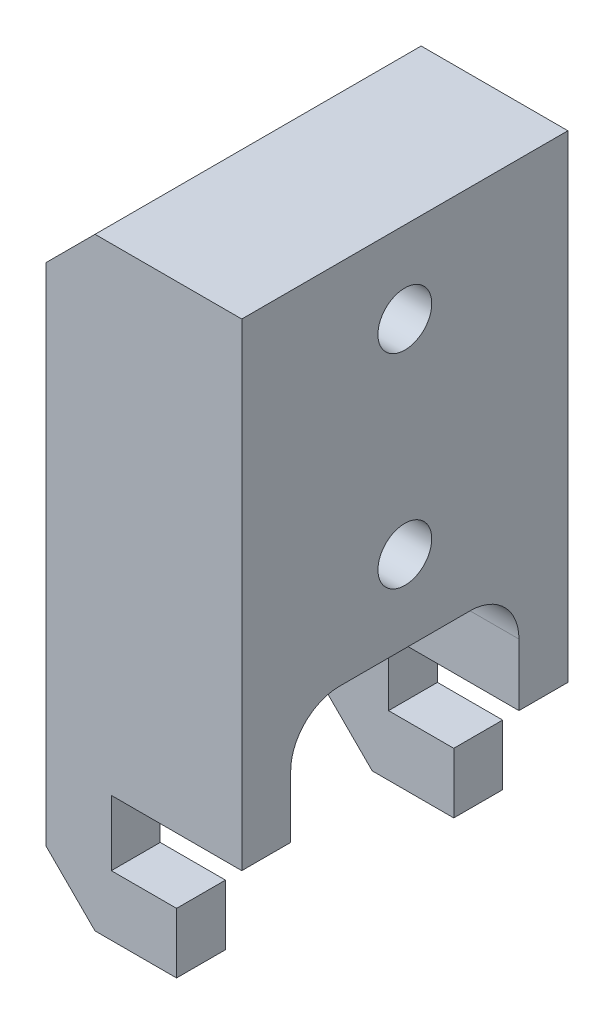
SolidWorks part; units mm, degrees
ref_plane "Front" through (0, 0, 0) normal (0, 0, 1) x (1, 0, 0)
ref_plane "Top" through (0, 0, 0) normal (0, 1, 0) x (1, 0, 0)
ref_plane "Right" through (0, 0, 0) normal (1, 0, 0) x (0, 0, -1)
sketch "Sketch1" plane through (0, 0, 0) normal (1, 0, 0) x (0, 0, -1)
  line L0 (-10, -18.5) -> (10, -18.5)
  line L1 (10, -18.5) -> (10, 18.5)
  line L2 (10, 18.5) -> (-10, 18.5)
  line L3 (-10, 18.5) -> (-10, -18.5)
  line L4 (0, 18.5) -> (0, 0) construction
  line L5 (0, 0) -> (10, 0) construction
  dimension "D1" = 37
  dimension "D2" = 20
extrude "Boss-Extrude1" add sketch "Sketch1" along normal blind 12
sketch "Sketch2" plane through (0, -18.5, 0) normal (0, -1, 0) x (1, 0, 0)
  line L0 (12, -7) -> (12, 7)
  line L1 (12, 7) -> (0, 7)
  line L2 (0, 7) -> (0, -7)
  line L3 (0, -7) -> (12, -7)
  line L4 (12, 10) -> (12, -10) construction
  line L5 (0, 10) -> (0, -10) construction
  line L6 (0, 0) -> (12, 0) construction
  dimension "D1" = 14
extrude "Cut-Extrude1" cut sketch "Sketch2" against normal blind 14.5
chamfer "Chamfer1" distance 3 angle 45 3 edges at (0, 18.5, 0) (0, -18.5, 8.5) (0, -18.5, -8.5)
fillet "Fillet1" radius 3 2 edges at (6, -4, -7) (6, -4, 7)
sketch "Sketch3" plane through (12, 0, 0) normal (1, 0, 0) x (0, 0, -1)
  line L0 (-7, -18.5) -> (-7, -10.8)
  line L1 (-7, -10.8) -> (-10, -10.8)
  line L2 (-10, -10.8) -> (-10, -18.5)
  line L3 (-10, -18.5) -> (-7, -18.5)
  line L4 (7, -18.5) -> (10, -18.5)
  line L5 (10, -18.5) -> (10, -10.8)
  line L6 (10, -10.8) -> (7, -10.8)
  line L7 (7, -10.8) -> (7, -18.5)
  line L8 (-10, -18.5) -> (-7, -18.5) construction
  line L9 (-7, -7) -> (-7, -18.5) construction
  line L10 (-10, 18.5) -> (-10, -18.5) construction
  line L11 (7, -7) -> (7, -18.5) construction
  line L12 (10, -18.5) -> (10, 18.5) construction
  dimension "D1" = 7.7
extrude "Cut-Extrude2" cut sketch "Sketch3" against normal blind 4
sketch "Sketch4" plane through (8, 0, 0) normal (1, 0, 0) x (0, 0, -1)
  line L0 (-7, -10.8) -> (-10, -10.8)
  line L1 (-10, -10.8) -> (-10, -14.8)
  line L2 (-10, -14.8) -> (-7, -14.8)
  line L3 (-7, -14.8) -> (-7, -10.8)
  line L4 (7, -14.8) -> (10, -14.8)
  line L5 (10, -14.8) -> (10, -10.8)
  line L6 (10, -10.8) -> (7, -10.8)
  line L7 (7, -10.8) -> (7, -14.8)
  line L8 (-7, -18.5) -> (-7, -10.8) construction
  line L9 (-10, -10.8) -> (-10, -18.5) construction
  line L10 (-7, -10.8) -> (-10, -10.8) construction
  line L11 (7, -10.8) -> (7, -18.5) construction
  line L12 (10, -18.5) -> (10, -10.8) construction
  dimension "D1" = 4
extrude "Cut-Extrude3" cut sketch "Sketch4" against normal blind 4
hole_wizard "Ø3.3 (3.3) Diameter Hole1" positions "Sketch6" profile "Sketch5" hole size "Ø3.3" standard "ANSI Metric"
sketch "Sketch6" plane through (12, 0, 0) normal (1, 0, 0) x (0, 0, -1)
  line L0 (0, 1) -> (0, 13.5) construction
  point P0 (0, 1)
  point P1 (0, 13.5)
  dimension "D1" = 1
  dimension "D2" = 12.5
sketch "Sketch5" plane through (12, 1, 0) normal (0, 1, 0) x (0, 0, -1)
  line L0 (0, 0) -> (0, 8.9914)
  line L1 (0, 8.9914) -> (1.65, 8)
  line L2 (1.65, 8) -> (1.65, 0)
  line L5 (1.65, 0) -> (0, 0)
  line L10 (0, 8.9914) -> (-1.65, 8) construction
  line L11 (0, -6.35) -> (0, 107.95) construction
  dimension "Hole Dia." = 3.3
  dimension "Hole Depth" = 8
  dimension "Drill Angle" = 118
